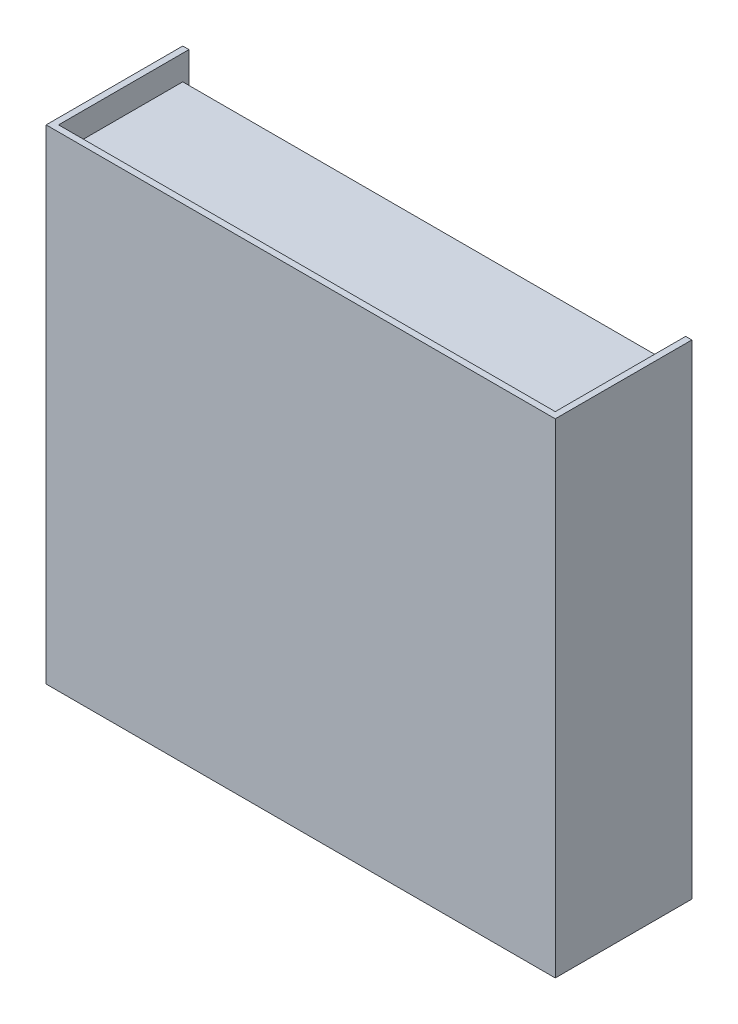
SolidWorks part; units mm, degrees
ref_plane "Front Plane" through (0, 0, 0) normal (0, 0, 1) x (1, 0, 0)
ref_plane "Top Plane" through (0, 0, 0) normal (0, 1, 0) x (1, 0, 0)
ref_plane "Right Plane" through (0, 0, 0) normal (1, 0, 0) x (0, 0, -1)
sketch "Sketch1" plane through (0, 0, 0) normal (0, 0, 1) x (1, 0, 0)
  line L0 (-512.8993, -399.9788) -> (503.1007, -399.9788)
  line L2 (-512.8993, -463.4788) -> (-512.8993, -399.9788)
  line L3 (-512.8993, 450.9212) -> (503.1007, 450.9212)
  line L4 (503.1007, -463.4788) -> (503.1007, -399.9788)
  line L8 (-525.5993, -476.1788) -> (-525.5993, 463.6212)
  line L9 (-525.5993, 463.6212) -> (515.8007, 463.6212)
  line L10 (515.8007, -476.1788) -> (515.8007, 463.6212)
  line L13 (-512.8993, -387.2788) -> (503.1007, -387.2788)
  line L14 (-525.5993, -476.1788) -> (-512.8993, -476.1788)
  line L15 (-512.8993, -476.1788) -> (-512.8993, -463.4788)
  line L16 (503.1007, -463.4788) -> (503.1007, -476.1788)
  line L17 (503.1007, -476.1788) -> (515.8007, -476.1788)
  line L18 (503.1007, -387.2788) -> (503.1007, 25.4712)
  line L19 (-512.8993, -387.2788) -> (-512.8993, 25.4712)
  line L20 (-512.8993, 38.1712) -> (-512.8993, 450.9212)
  line L21 (-512.8993, 38.1712) -> (503.1007, 38.1712)
  line L22 (-512.8993, 25.4712) -> (503.1007, 25.4712)
  line L23 (503.1007, 38.1712) -> (503.1007, 450.9212)
  point P0 (0, 0)
  point P6 (0, 0)
  dimension "D1" = 914.4
  dimension "D2" = 1016
  dimension "D3" = 12.7
  dimension "D4" = 12.7
  dimension "D5" = 12.7
  dimension "D8" = 12.7
extrude "Boss-Extrude2" add sketch "Sketch1" along normal blind 203.2
sketch "Sketch3" plane through (0, 0, 203.2) normal (0, 0, 1) x (1, 0, 0)
  line L1 (-525.5993, 463.6212) -> (515.8007, 463.6212)
  line L2 (-525.5993, 463.6212) -> (-525.5993, -476.1788)
  line L3 (-525.5993, -476.1788) -> (515.8007, -476.1788)
  line L4 (515.8007, 463.6212) -> (515.8007, -476.1788)
extrude "Boss-Extrude4" add sketch "Sketch3" along normal blind 25.4
sketch "Sketch6" plane through (0, 0, 0) normal (0, 0, -1) x (-1, 0, 0)
  line L1 (-515.8007, 463.6212) -> (-503.1007, 463.6212)
  line L2 (-515.8007, 463.6212) -> (-515.8007, -476.1788)
  line L3 (-515.8007, -476.1788) -> (-503.1007, -476.1788)
  line L4 (-503.1007, 463.6212) -> (-503.1007, -476.1788)
extrude "Boss-Extrude7" add sketch "Sketch6" along normal blind 50.8
sketch "Sketch7" plane through (0, 0, 0) normal (0, 0, -1) x (-1, 0, 0)
  line L1 (525.5993, 463.6212) -> (512.8993, 463.6212)
  line L2 (525.5993, 463.6212) -> (525.5993, -476.1788)
  line L3 (525.5993, -476.1788) -> (512.8993, -476.1788)
  line L4 (512.8993, 463.6212) -> (512.8993, -476.1788)
extrude "Boss-Extrude8" add sketch "Sketch7" along normal blind 50.8
sketch "Sketch8" plane through (0, 463.6212, 0) normal (0, 1, 0) x (1, 0, 0)
  line L0 (515.8007, -228.6) -> (-525.5993, -228.6) construction
  line L6 (-512.8993, 0) -> (-512.8993, -215.9)
  line L7 (-512.8993, -215.9) -> (503.1007, -215.9)
  line L8 (503.1007, 0) -> (503.1007, -215.9)
  line L10 (-525.5993, -228.6) -> (-525.5993, 50.8) construction
  line L11 (515.8007, -228.6) -> (-525.5993, -228.6)
  line L12 (515.8007, -228.6) -> (515.8007, 0)
  line L14 (-525.5993, -228.6) -> (-525.5993, 0)
  line L16 (515.8007, 0) -> (515.8007, 50.8)
  line L17 (515.8007, 50.8) -> (503.1007, 50.8)
  line L18 (503.1007, 50.8) -> (503.1007, 0)
  line L19 (-512.8993, 0) -> (-512.8993, 50.8)
  line L20 (-512.8993, 50.8) -> (-525.5993, 50.8)
  line L21 (-525.5993, 50.8) -> (-525.5993, 0)
  dimension "D1" = 12.7
extrude "Boss-Extrude9" add sketch "Sketch8" along normal blind 50.8
sketch "Sketch10" plane through (0, 0, 0) normal (0, 0, -1) x (-1, 0, 0)
  line L1 (512.8993, -476.1788) -> (-503.1007, -476.1788)
  line L2 (512.8993, -476.1788) -> (512.8993, 38.1712)
  line L3 (512.8993, 38.1712) -> (-503.1007, 38.1712)
  line L4 (-503.1007, -476.1788) -> (-503.1007, 38.1712)
extrude "Cut-Extrude1" cut sketch "Sketch10" against normal blind 50.8
sketch "Sketch11" plane through (0, 0, 0) normal (0, 0, -1) x (-1, 0, 0)
  line L1 (-503.1007, 463.6212) -> (512.8993, 463.6212)
  line L2 (-503.1007, 463.6212) -> (-503.1007, 450.9212)
  line L3 (-503.1007, 450.9212) -> (512.8993, 450.9212)
  line L4 (512.8993, 463.6212) -> (512.8993, 450.9212)
extrude "Boss-Extrude11" add sketch "Sketch11" along normal blind 38.1
sketch "Sketch13" plane through (0, 0, 50.8) normal (0, 0, -1) x (-1, 0, 0)
  line L0 (512.8993, 514.4212) -> (512.8993, -476.1788) construction
  line L1 (-503.1007, 25.4712) -> (512.8993, 25.4712)
  line L2 (-503.1007, 25.4712) -> (-503.1007, 101.6712)
  line L3 (-503.1007, 101.6712) -> (512.8993, 101.6712)
  line L4 (512.8993, 25.4712) -> (512.8993, 101.6712)
  line L6 (-503.1007, -399.9788) -> (512.8993, -399.9788)
  line L7 (-503.1007, -399.9788) -> (-503.1007, -323.7788)
  line L8 (-503.1007, -323.7788) -> (512.8993, -323.7788)
  line L9 (512.8993, -399.9788) -> (512.8993, -323.7788)
  dimension "D1" = 76.2
  dimension "D2" = 76.2
extrude "Boss-Extrude12" add sketch "Sketch13" against normal blind 12.7
